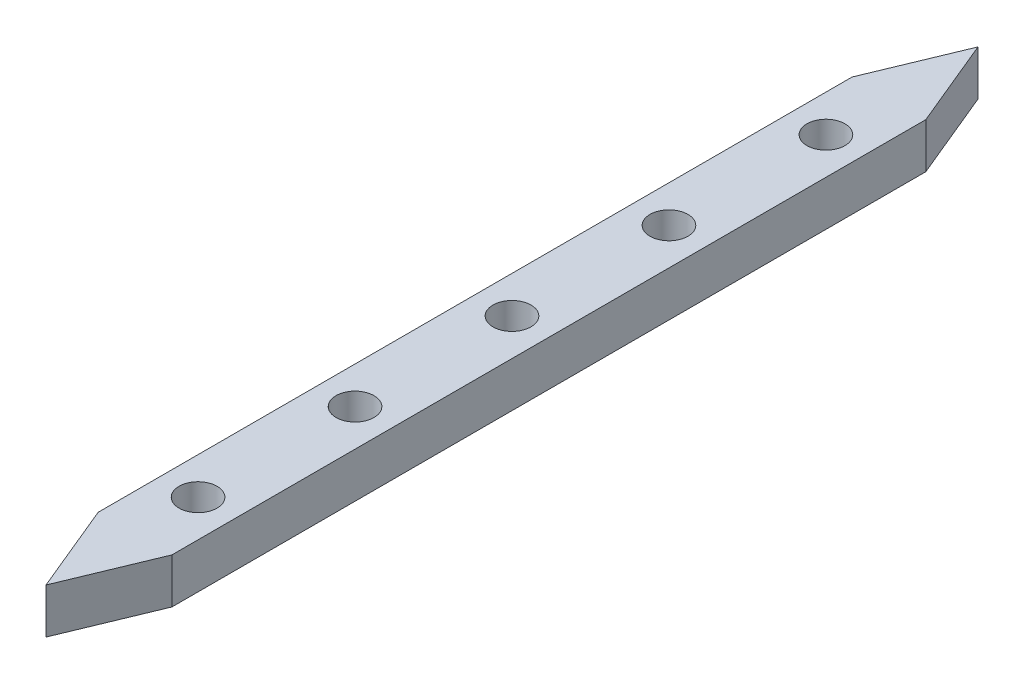
SolidWorks part; units mm, degrees
material "PE Low/Medium Density"
ref_plane "Front Plane" through (0, 0, 0) normal (0, 0, 1) x (1, 0, 0)
ref_plane "Top Plane" through (0, 0, 0) normal (0, 1, 0) x (1, 0, 0)
ref_plane "Right Plane" through (0, 0, 0) normal (1, 0, 0) x (0, 0, -1)
sketch "Sketch1" plane through (0, 0, 0) normal (0, 1, 0) x (1, 0, 0)
  line L0 (0, 60.325) -> (0, -48.1572) construction
  line L1 (0, 60.325) -> (-4.7752, 48.7966)
  line L2 (-4.7752, 48.7966) -> (-4.7752, -48.7966)
  line L3 (-28.5797, 0) -> (23.9031, 0) construction
  line L4 (0, -60.325) -> (-4.7752, -48.7966)
  line L5 (0, -60.325) -> (4.7752, -48.7966)
  line L6 (4.7752, 48.7966) -> (4.7752, -48.7966)
  line L7 (0, 60.325) -> (4.7752, 48.7966)
  point P9 (-4.7752, 0)
  point P10 (4.7752, 0)
  dimension "D1" = 9.5504
  dimension "D2" = 120.65
  dimension "D3" = 22.5
extrude "Boss-Extrude1" add sketch "Sketch1" along normal blind 5.842
hole_wizard "#10 (0.1935) Diameter Hole1" positions "Sketch4" profile "Sketch5" hole size "#10" standard "ANSI Inch" end condition through all
sketch "Sketch4" plane through (0, 5.842, 0) normal (0, 1, 0) x (1, 0, 0)
  line L0 (-4.7752, 0) -> (4.7752, 0) construction
  line L1 (-4.7752, 48.7966) -> (-4.7752, -48.7966) construction
  line L2 (4.7752, -48.7966) -> (4.7752, 48.7966) construction
  point P0 (0, 20.32)
  point P2 (0, 40.64)
  point P14 (0, 0)
  point P16 (0, -20.32)
  point P18 (0, -40.64)
  dimension "D1" = 20.32
  dimension "D2" = 40.64
  dimension "D3" = 20.32
  dimension "D4" = 40.64
sketch "Sketch5" plane through (0, 5.842, -20.32) normal (1, 0, 0) x (0, 0, 1)
  line L0 (0, 0) -> (0, 5.842)
  line L1 (0, 5.842) -> (2.4574, 5.842)
  line L2 (2.4574, 5.842) -> (2.4574, 0)
  line L5 (2.4574, 0) -> (0, 0)
  line L11 (0, -6.35) -> (0, 107.95) construction
  dimension "Thru Hole Dia." = 4.9149
  dimension "Thru Hole Depth" = 5.842
